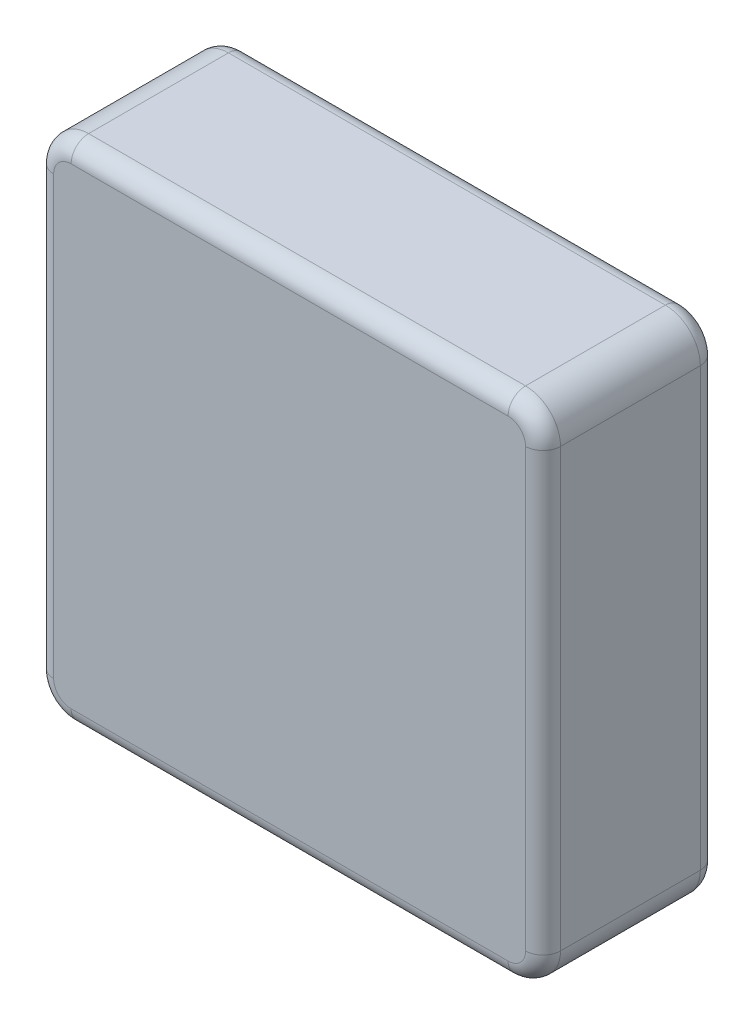
SolidWorks part; units mm, degrees
material "Alliage 1060"
ref_plane "Face" through (0, 0, 0) normal (0, 0, 1) x (1, 0, 0)
ref_plane "Dessus" through (0, 0, 0) normal (0, 1, 0) x (1, 0, 0)
ref_plane "Droite" through (0, 0, 0) normal (1, 0, 0) x (0, 0, -1)
sketch "Esquisse1" plane through (0, 0, 0) normal (0, 0, 1) x (1, 0, 0)
  line L1 (-14.5, 14.5) -> (14.5, 14.5)
  line L2 (-14.5, 14.5) -> (-14.5, -14.5)
  line L3 (-14.5, -14.5) -> (14.5, -14.5)
  line L4 (14.5, 14.5) -> (14.5, -14.5)
  dimension "D1" = 14.5
  dimension "D2" = 29
  dimension "D3" = 14.5
  dimension "D4" = 29
extrude "Boss.-Extru.1" add sketch "Esquisse1" along normal blind 10
hole_wizard "Trou taraudé M32" positions "Esquisse4" profile "Esquisse3" tap size "M3" standard "Iso"
sketch "Esquisse4" plane through (0, 0, 0) normal (0, 0, -1) x (-1, 0, 0)
  point P0 (-11, 11)
  point P2 (11, -11)
  dimension "D1" = 11
  dimension "D2" = 11
  dimension "D3" = 11
  dimension "D4" = 11
sketch "Esquisse3" plane through (11, 11, 0) normal (1, 0, 0) x (0, 1, 0)
  line L0 (0, 0) -> (0, 9.2511)
  line L1 (0, 9.2511) -> (1.25, 8.5)
  line L2 (1.25, 8.5) -> (1.25, 0)
  line L5 (1.25, 0) -> (0, 0)
  line L10 (0, 9.2511) -> (-1.25, 8.5) construction
  line L11 (0, -6.35) -> (0, 107.95) construction
  dimension "Diamètre du trou pour taraudage" = 2.5
  dimension "Profondeur du trou pour taraudage" = 8.5
  dimension "Angle de pointe" = 118
cosmetic thread "Filetage de perçage5" parameters "D1"=6, "D2"=3
cosmetic thread "Filetage de perçage6" parameters "D1"=6, "D2"=3
fillet "Congé 2" radius 2 4 edges at (-14.5, -14.5, 5) (14.5, -14.5, 5) (14.5, 14.5, 5) (-14.5, 14.5, 5)
fillet "Congé1" radius 1 16 edges at (13.9142, 13.9142, 0) (14.5, 0, 0) (13.9142, -13.9142, 0) (0, -14.5, 0) (-13.9142, -13.9142, 0) (-14.5, 0, 0) (-13.9142, 13.9142, 0) (0, 14.5, 0) (-13.9142, 13.9142, 10) (0, 14.5, 10) (13.9142, 13.9142, 10) (14.5, 0, 10) (13.9142, -13.9142, 10) (0, -14.5, 10) (-13.9142, -13.9142, 10) (-14.5, 0, 10)
